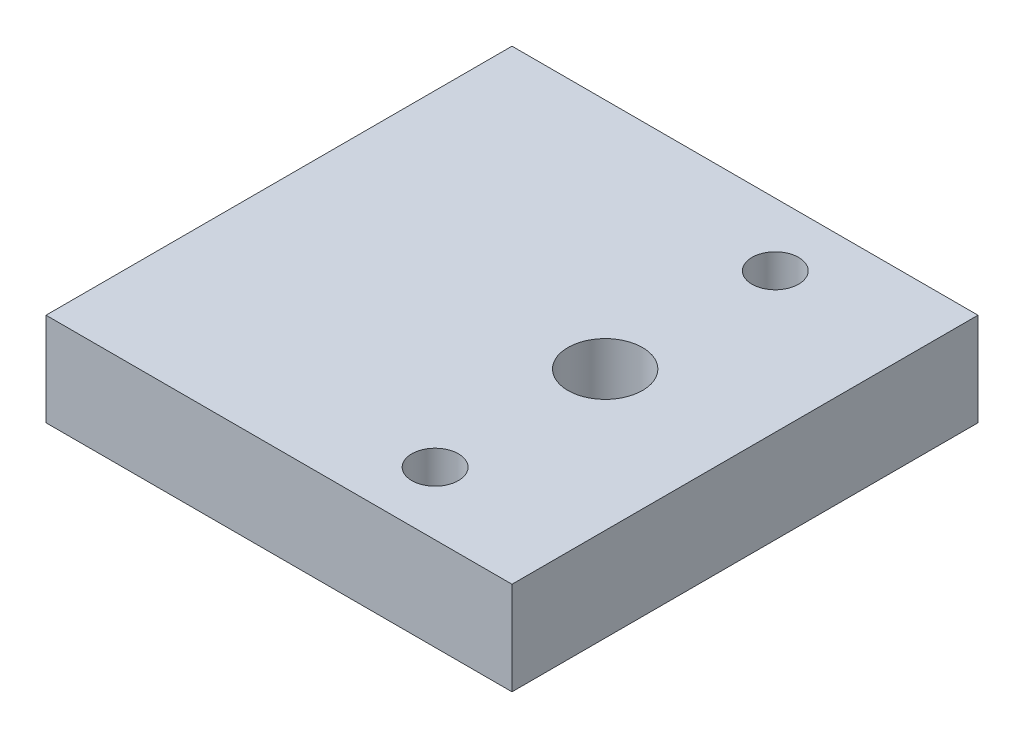
SolidWorks part; units mm, degrees
ref_plane "Plano frontal" through (0, 0, 0) normal (0, 0, 1) x (1, 0, 0)
ref_plane "Plano superior" through (0, 0, 0) normal (0, 1, 0) x (1, 0, 0)
ref_plane "Plano direito" through (0, 0, 0) normal (1, 0, 0) x (0, 0, -1)
sketch "Esboço2" plane through (0, 0, 0) normal (0, 1, 0) x (1, 0, 0)
  line L1 (-25, -25) -> (25, -25)
  line L2 (-25, -25) -> (-25, 25)
  line L3 (-25, 25) -> (25, 25)
  line L4 (25, -25) -> (25, 25)
  line L5 (-25, -25) -> (25, 25) construction
  line L6 (-25, 25) -> (25, -25) construction
  point P0 (0, 0)
  dimension "D1" = 50
  dimension "D2" = 50
extrude "Ressalto-extrusão2" add sketch "Esboço2" along normal blind 10
sketch "Esboço5" plane through (0, 10, 0) normal (0, 1, 0) x (1, 0, 0)
  line L0 (10, 27.5237) -> (10, -26.8195) construction
  line L1 (-30.6203, 0) -> (34.1735, 0) construction
  line L2 (25, -25) -> (25, 25) construction
  circle A0 centre (10, 18.25) radius 2.5
  circle A1 centre (10, -18.25) radius 2.5
  dimension "D1" = 5
  dimension "D2" = 5
  dimension "D3" = 18.25
  dimension "D4" = 18.25
  dimension "D5" = 15
extrude "Corte-extrusão5" cut sketch "Esboço5" against normal through all
sketch "Esboço6" plane through (0, 10, 0) normal (0, 1, 0) x (1, 0, 0)
  line L0 (25, -25) -> (25, 25) construction
  line L1 (-25, -25) -> (25, -25) construction
  circle A0 centre (10, 0) radius 4
  dimension "D1" = 8
  dimension "D2" = 15
  dimension "D3" = 25
extrude "Corte-extrusão6" cut sketch "Esboço6" against normal blind 10
